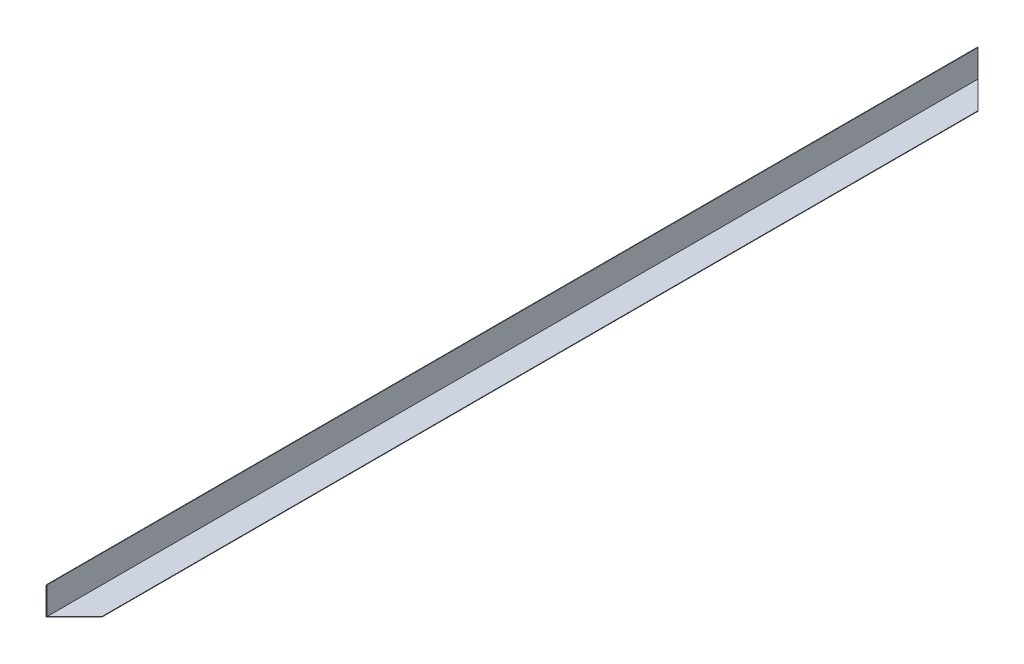
SolidWorks part; units mm, degrees
ref_plane "Front Plane" through (0, 0, 0) normal (0, 0, 1) x (1, 0, 0)
ref_plane "Top Plane" through (0, 0, 0) normal (0, 1, 0) x (1, 0, 0)
ref_plane "Right Plane" through (0, 0, 0) normal (1, 0, 0) x (0, 0, -1)
sketch "Sketch1" plane through (0, 0, 0) normal (0, 0, 1) x (1, 0, 0)
  line L0 (0, 45) -> (0, 0)
  line L1 (0, 0) -> (45, 0)
  line L2 (45, 0) -> (45, 0.8333)
  line L3 (45, 0.8333) -> (0.8333, 0.8333)
  line L4 (0.8333, 0.8333) -> (0.8333, 45)
  line L5 (0.8333, 45) -> (0, 45)
  dimension "D1" = 45
  dimension "D2" = 45
  dimension "D3" = 0.8333
  dimension "D4" = 0.8333
extrude "Boss-Extrude1" add sketch "Sketch1" along normal mid plane 1510
sketch "Sketch2" plane through (0, 0.8333, 0) normal (0, 1, 0) x (1, 0, 0)
  line L0 (0.8333, -750) -> (45, -705.8333)
  line L1 (0.8333, -755) -> (0.8333, 755) construction
  line L2 (45, -755) -> (45, 755) construction
  line L3 (-24.75, 0) -> (24.75, 0) construction
  line L4 (0.8333, 750) -> (45, 705.8333)
  dimension "D1" = 45
  dimension "D2" = 1500
ref_plane "Plane1" through (375.4167, 0, -375.4167) normal (-0.7071, 0, 0.7071) x (0.7071, 0, 0.7071)
other "SurfaceCut1"
ref_plane "Plane2" through (375.4167, 0, 375.4167) normal (0.7071, 0, 0.7071) x (0.7071, 0, -0.7071)
other "SurfaceCut2"
